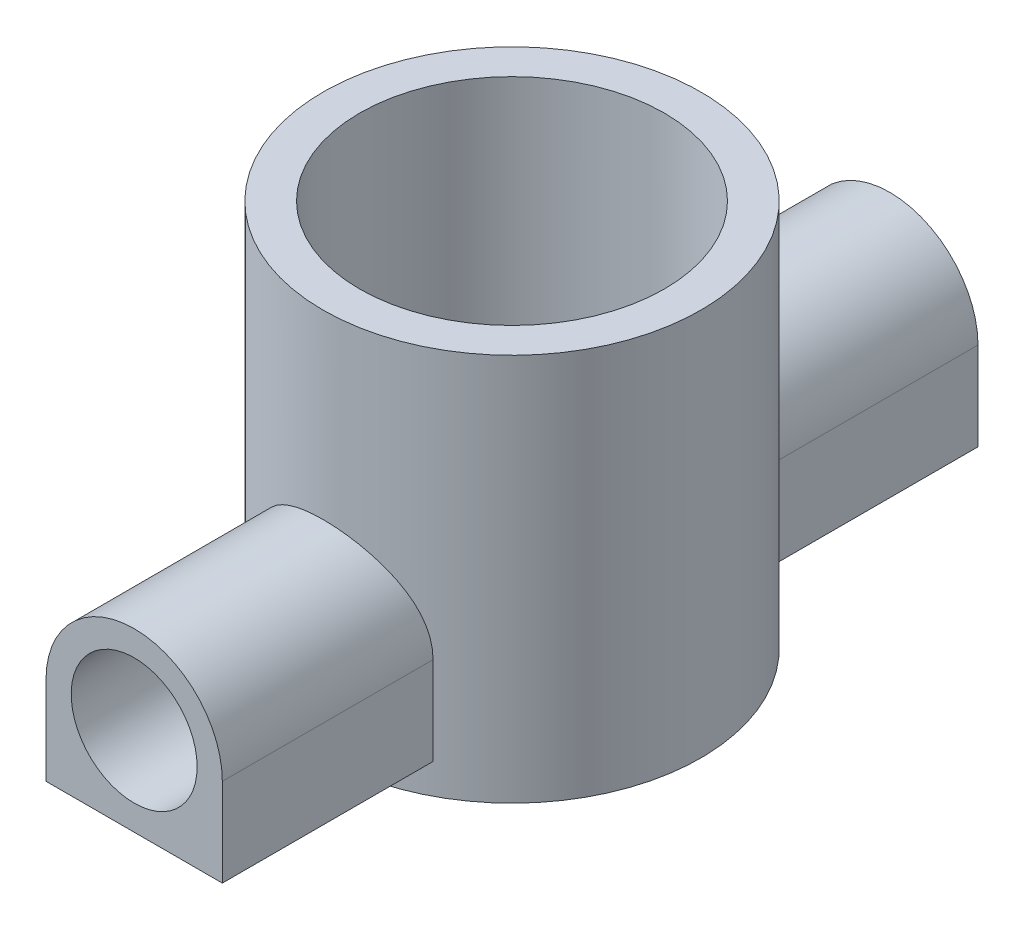
SolidWorks part; units mm, degrees
material "PET"
ref_plane "Ebene vorne" through (0, 0, 0) normal (0, 0, 1) x (1, 0, 0)
ref_plane "Ebene oben" through (0, 0, 0) normal (0, 1, 0) x (1, 0, 0)
ref_plane "Ebene rechts" through (0, 0, 0) normal (1, 0, 0) x (0, 0, -1)
sketch "Sketch1" plane through (0, 0, 0) normal (0, 1, 0) x (1, 0, 0)
  circle A0 centre (0, 0) radius 7.5
  dimension "D1" = 15
extrude "base-cylinder" add sketch "Sketch1" along normal blind 15.4
sketch3d "3DSketch2"
  line L0 (0, 0, 7.5) -> (0, 1.2, 7.5)
  line L1 (0, 1.2, 7.5) -> (0, 4.7, 7.5)
  line L2 (0, 0, -15) -> (0, 0, 15)
  line L3 (-3.5, 4.7, 7.5) -> (3.5, 4.7, 7.5)
  line L4 (-3.5, 4.7, 7.5) -> (-3.5, 1.2, 7.5)
  line L5 (3.5, 4.7, 7.5) -> (3.5, 1.2, 7.5)
  line L6 (-3.5, 1.2, 7.5) -> (3.5, 1.2, 7.5)
  circle A0 centre (0, 0, 0) radius 7.5 construction
  circle A1 centre (0, 4.7, 7.5) radius 3.5
  point P4 (0, 7.5, 0)
  point P7 (0, 4.7, 11)
  point P10 (0, 1.2, 7.5)
  point P13 (0, 4.7, 7.5)
  point P18 (0, 0, 0)
  dimension "D4" = 3.5
  dimension "D1" = 1.2
  dimension "D2" = 3.5
  dimension "D3" = 30
extrude "led-holder" add sketch "3DSketch2" along direction (0, 0, 1) on the side of the normal blind 7.5 and the other way blind 22.5 contours A1 | L4 L6 L5 L3
sketch "Sketch2" plane through (0, 15.4, 0) normal (0, 1, 0) x (1, 0, 0)
  circle A0 centre (0, 0) radius 6.05
  dimension "D1" = 12.1
extrude "Cut-Extrude1" cut sketch "Sketch2" against normal blind 14.2
sketch "Sketch3" plane through (0, 0, 0) normal (0, -1, 0) x (1, 0, 0)
  circle A0 centre (0, 0) radius 1.75
  dimension "D1" = 3.5
extrude "Cut-Extrude2" cut sketch "Sketch3" against normal up to next
sketch "Sketch4" plane through (0, 0, -15) normal (0, 0, -1) x (-1, 0, 0)
  line L0 (-3.5, 4.7) -> (3.5, 4.7) construction
  circle A0 centre (0, 4.7) radius 2.5
  dimension "D1" = 5
extrude "Cut-Extrude3" cut sketch "Sketch4" against normal through all
